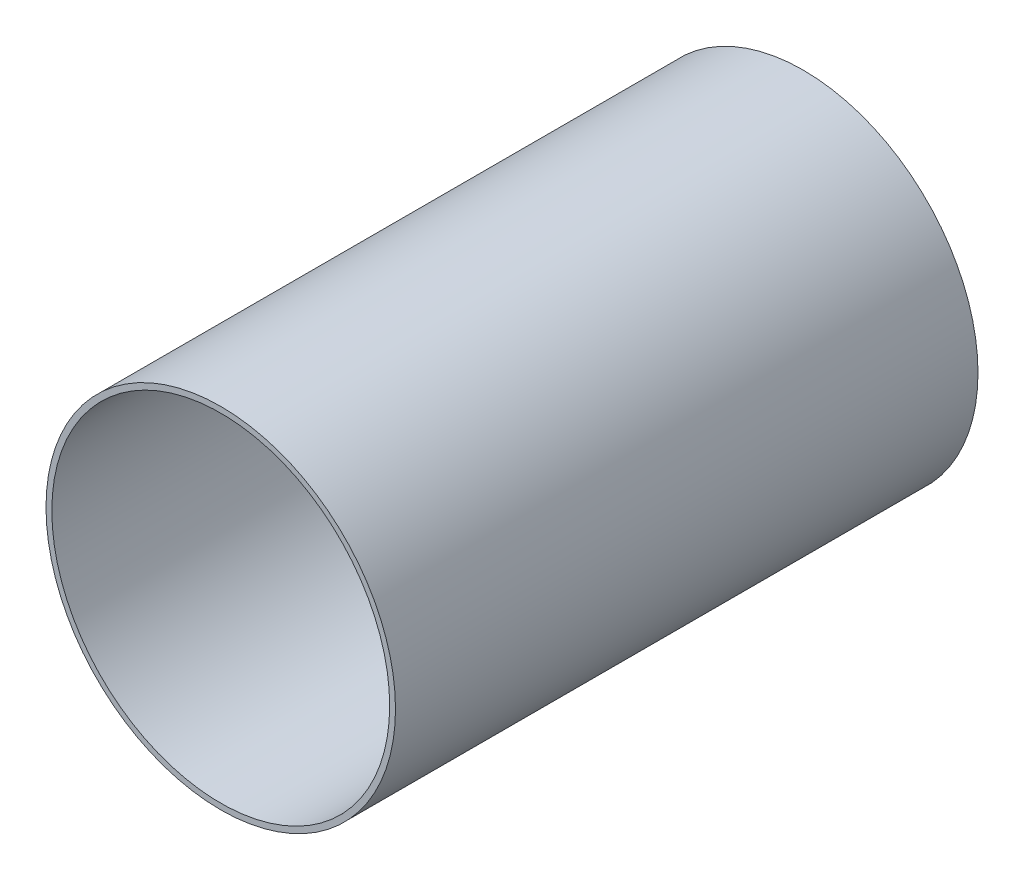
SolidWorks part; units mm, degrees
ref_plane "Front Plane" through (0, 0, 0) normal (0, 0, 1) x (1, 0, 0)
ref_plane "Top Plane" through (0, 0, 0) normal (0, 1, 0) x (1, 0, 0)
ref_plane "Right Plane" through (0, 0, 0) normal (1, 0, 0) x (0, 0, -1)
sketch "Sketch1" plane through (0, 0, 0) normal (0, 0, 1) x (1, 0, 0)
  circle A0 centre (0, 0) radius 1.5
  circle A1 centre (0, 0) radius 1.45
  dimension "D1" = 2.9
extrude "Boss-Extrude1" add sketch "Sketch1" along normal blind 5
